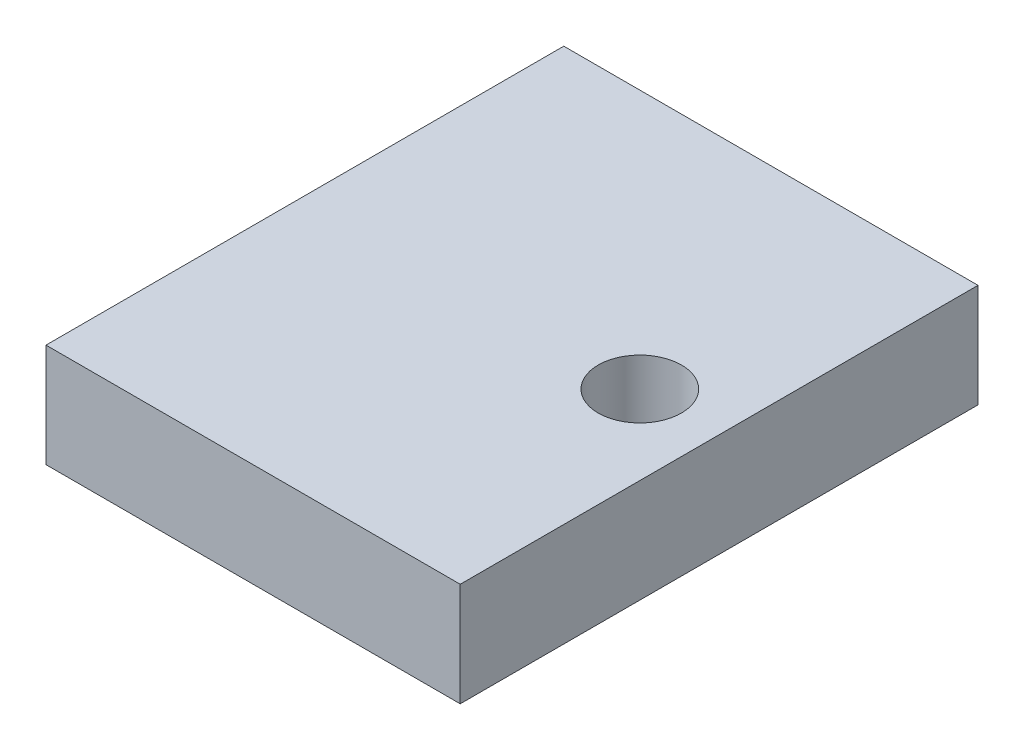
SolidWorks part; units mm, degrees
ref_plane "Front Plane" through (0, 0, 0) normal (0, 0, 1) x (1, 0, 0)
ref_plane "Top Plane" through (0, 0, 0) normal (0, 1, 0) x (1, 0, 0)
ref_plane "Right Plane" through (0, 0, 0) normal (1, 0, 0) x (0, 0, -1)
sketch "Sketch2" plane through (0, 0, 0) normal (0, 1, 0) x (1, 0, 0)
  line L1 (0, 0) -> (25.4, 0)
  line L2 (0, 0) -> (0, 31.75)
  line L3 (0, 31.75) -> (25.4, 31.75)
  line L12 (25.4, 31.75) -> (25.4, 0)
  dimension "D1" = 25.4
  dimension "D2" = 31.75
extrude "Boss-Extrude1" add sketch "Sketch2" along normal blind 6.35
hole_wizard "1/4-20 Tapped Hole1" positions "3DSketch1" profile "Sketch3" tap size "1/4-20" standard "ANSI Inch"
sketch3d "3DSketch1"
  line L0 (0, 6.35, -31.75) -> (25.4, 6.35, -31.75) construction
  line L1 (25.4, 6.35, -31.75) -> (25.4, 6.35, 0) construction
  point P0 (20.5392, 6.35, -15.875)
  dimension "D1" = 15.875
  dimension "D2" = 4.8608
sketch "Sketch3" plane through (20.5392, 6.35, -15.875) normal (1, 0, 0) x (0, 0, 1)
  line L0 (0, 0) -> (0, 20.5838)
  line L1 (0, 20.5838) -> (2.5527, 19.05)
  line L2 (2.5527, 19.05) -> (2.5527, 0)
  line L5 (2.5527, 0) -> (0, 0)
  line L10 (0, 20.5838) -> (-2.5527, 19.05) construction
  line L11 (0, -6.35) -> (0, 107.95) construction
  dimension "Tap Drill Dia." = 5.1054
  dimension "Tap Drill Depth" = 19.05
  dimension "Drill Angle" = 118
cosmetic thread "Hole Thread1" parameters "D1"=6.35, "D2"=6.35
